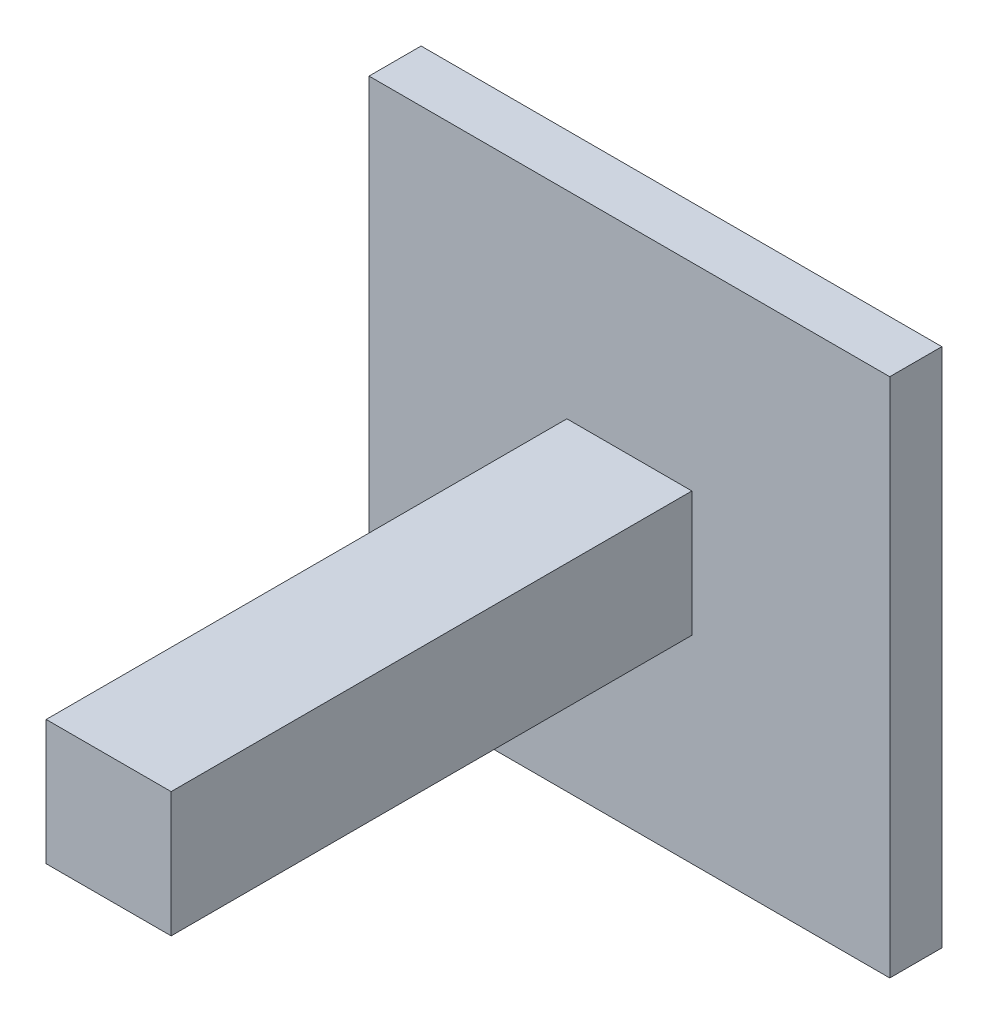
SolidWorks part; units mm, degrees
ref_plane "Face" through (0, 0, 0) normal (0, 0, 1) x (1, 0, 0)
ref_plane "Dessus" through (0, 0, 0) normal (0, 1, 0) x (1, 0, 0)
ref_plane "Droite" through (0, 0, 0) normal (1, 0, 0) x (0, 0, -1)
sketch "Esquisse1" plane through (0, 0, 0) normal (0, 0, 1) x (1, 0, 0)
  line L0 (0, 0) -> (0, 68.2715) construction
  line L1 (-25, 25) -> (25, 25)
  line L2 (25, 25) -> (25, -25)
  line L3 (0, 0) -> (62.352, 0) construction
  line L4 (-25, -25) -> (25, -25)
  line L5 (-25, 25) -> (-25, -25)
  point P8 (25, 0)
  point P10 (0, -25)
  point P11 (0, 25)
  dimension "D1" = 25
  dimension "D2" = 25
extrude "Base-Extrusion" add sketch "Esquisse1" along normal blind 5
sketch "Esquisse2" plane through (0, 0, 5) normal (0, 0, 1) x (1, 0, 0)
  line L0 (-6, 6) -> (6, 6)
  line L1 (6, 6) -> (6, -6)
  line L2 (0, 20.8705) -> (0, -9.201) construction
  line L3 (0, 0) -> (28.9494, 0) construction
  line L4 (-6, -6) -> (6, -6)
  line L5 (-6, 6) -> (-6, -6)
  point P10 (6, 0)
  point P11 (0, -6)
  point P12 (0, 6)
  dimension "D1" = 6
  dimension "D2" = 6
extrude "Boss.-Extru.1" add sketch "Esquisse2" along normal blind 50
